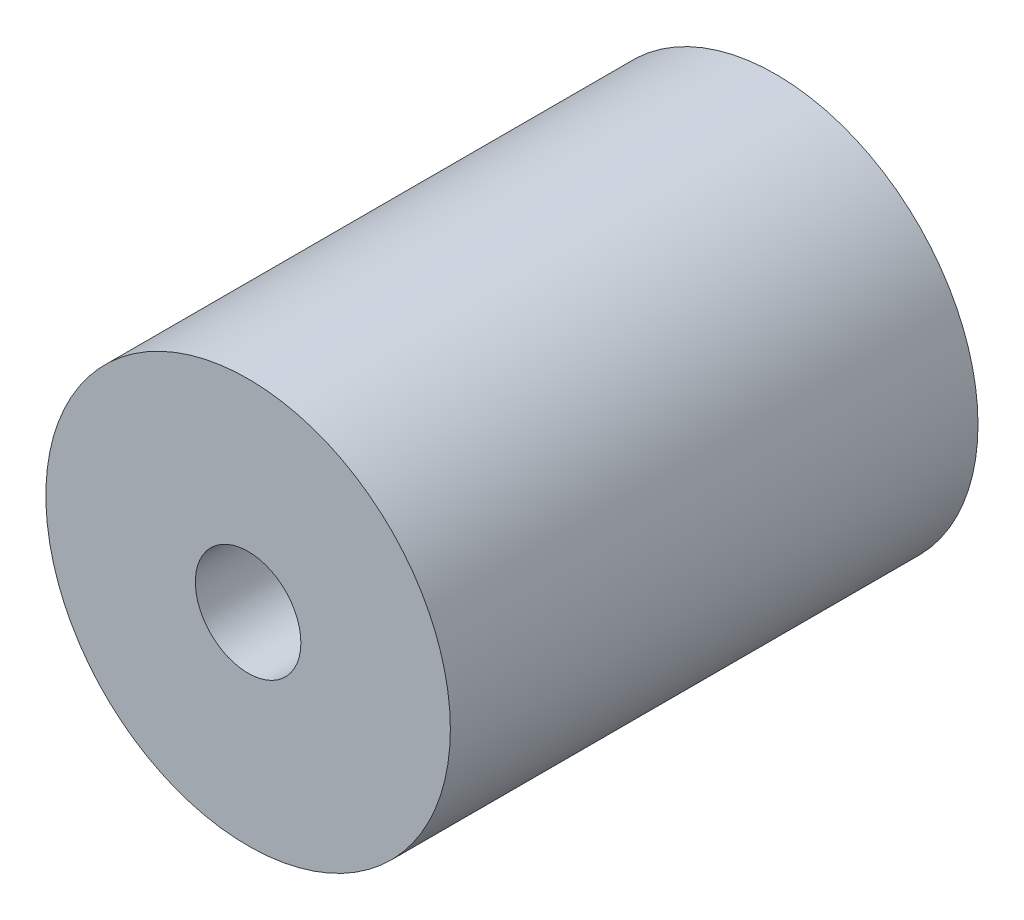
SolidWorks part; units mm, degrees
ref_plane "Piano frontale" through (0, 0, 0) normal (0, 0, 1) x (1, 0, 0)
ref_plane "Piano superiore" through (0, 0, 0) normal (0, 1, 0) x (1, 0, 0)
ref_plane "Piano destro" through (0, 0, 0) normal (1, 0, 0) x (0, 0, -1)
sketch "Schizzo1" plane through (0, 0, 0) normal (0, 0, 1) x (1, 0, 0)
  circle A0 centre (0, 0) radius 3
  circle A1 centre (0, 0) radius 11.5
  dimension "D1" = 23
  dimension "D2" = 6
extrude "Estrusione-Estrusione1" add sketch "Schizzo1" along normal blind 30
